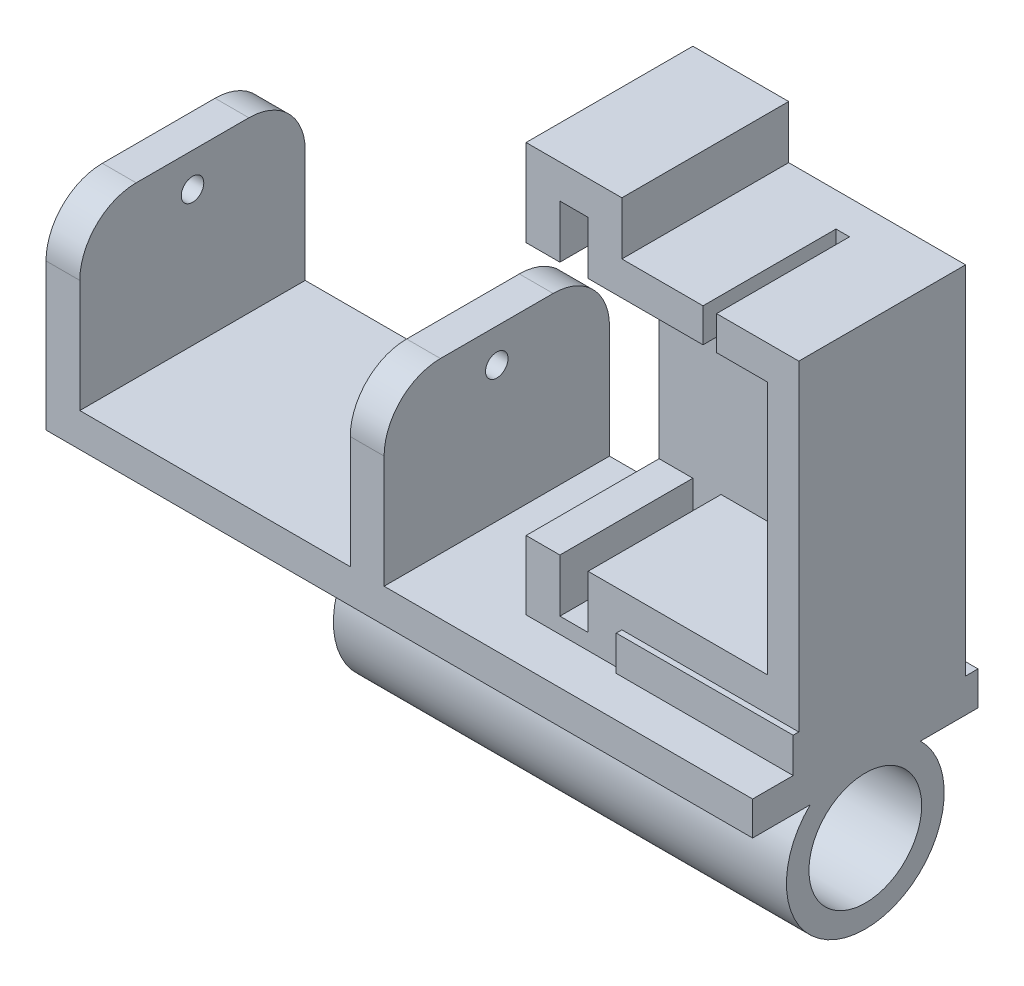
SolidWorks part; units mm, degrees
ref_plane "Front Plane" through (0, 0, 0) normal (0, 0, 1) x (1, 0, 0)
ref_plane "Top Plane" through (0, 0, 0) normal (0, 1, 0) x (1, 0, 0)
ref_plane "Right Plane" through (0, 0, 0) normal (1, 0, 0) x (0, 0, -1)
sketch "Sketch1" plane through (0, 0, 0) normal (0, 1, 0) x (1, 0, 0)
  line L1 (0, 0) -> (50, 0)
  line L2 (0, 0) -> (0, -20)
  line L3 (0, -20) -> (50, -20)
  line L4 (50, 0) -> (50, -20)
  dimension "D1" = 20
  dimension "D2" = 50
extrude "Boss-Extrude1" add sketch "Sketch1" along normal blind 3
sketch "Sketch2" plane through (0, 3, 0) normal (0, 1, 0) x (1, 0, 0)
  line L0 (0, -20) -> (50, -20) construction
  line L1 (0, 0) -> (3, 0)
  line L2 (0, 0) -> (0, -20)
  line L3 (0, -20) -> (3, -20)
  line L4 (3, 0) -> (3, -20)
  dimension "D1" = 3
extrude "Boss-Extrude2" add sketch "Sketch2" along normal blind 15
sketch "Sketch3" plane through (3, 0, 0) normal (1, 0, 0) x (0, 0, -1)
  circle A0 centre (-10, 15) radius 1
  dimension "D1" = 2
  dimension "D2" = 12
  dimension "D3" = 10
extrude "Cut-Extrude1" cut sketch "Sketch3" against normal blind 15
fillet "Fillet1" radius 5 2 edges at (1.5, 18, 0) (1.5, 18, 20)
sketch "Sketch4" plane through (0, 3, 0) normal (0, 1, 0) x (1, 0, 0)
  line L0 (3, -20) -> (50, -20) construction
  line L1 (27, -20) -> (30, -20)
  line L2 (27, -20) -> (27, 0)
  line L3 (27, 0) -> (30, 0)
  line L4 (30, -20) -> (30, 0)
  line L5 (50, 0) -> (3, 0) construction
  dimension "D1" = 3
  dimension "D2" = 30
extrude "Boss-Extrude3" add sketch "Sketch4" along normal blind 15
sketch "Sketch5" plane through (27, 0, 0) normal (-1, 0, 0) x (0, 0, 1)
  circle A0 centre (10, 15) radius 1
extrude "Cut-Extrude2" cut sketch "Sketch5" against normal blind 15
fillet "Fillet2" radius 5 2 edges at (28.5, 18, 20) (28.5, 18, 0)
ref_plane "Plane1" through (0, 0, 10) normal (0, 0, -1) x (-1, 0, 0)
sketch "Sketch6" plane through (0, 0, 10) normal (0, 0, -1) x (-1, 0, 0)
  line L0 (-3, 15) -> (-37.0484, 15)
  line L1 (-3, 16) -> (-3, 14) construction
  line L2 (-30, 12.7) -> (-30, 17.3)
  line L3 (-62.9, 34.6) -> (-47, 34.6)
  line L4 (-30, 17.3) -> (-33.2, 17.3)
  line L5 (-33.2, 17.3) -> (-33.2, 23.8)
  line L6 (-33.2, 23.8) -> (-37.2, 23.8)
  line L7 (-30, 12.7) -> (-33.2, 12.7)
  line L8 (-33.2, 12.7) -> (-33.2, 9.1)
  line L9 (-33.2, 9.1) -> (-41.5, 9.1)
  line L10 (-41.5, 9.1) -> (-41.5, 4.4)
  line L11 (-41.5, 4.4) -> (-44, 4.4)
  line L12 (-44, 4.4) -> (-44, 9.1)
  line L13 (-44, 9.1) -> (-59.9, 9.1)
  line L14 (-59.9, 9.1) -> (-59.9, 31.6)
  line L15 (-59.9, 31.6) -> (-44, 31.6)
  line L16 (-44, 31.6) -> (-44, 36.3)
  line L17 (-44, 36.3) -> (-41.5, 36.3)
  line L18 (-41.5, 36.3) -> (-41.5, 31.6)
  line L19 (-41.5, 31.6) -> (-37.2, 31.6)
  line L20 (-37.2, 31.6) -> (-37.2, 23.8)
  line L21 (-47, 34.6) -> (-47, 39.3)
  line L22 (-47, 39.3) -> (-38.5, 39.3)
  line L23 (-38.5, 39.3) -> (-38.5, 34.6)
  line L24 (-38.5, 34.6) -> (-34.2, 34.6)
  line L25 (-34.2, 34.6) -> (-34.2, 26.8)
  line L26 (-30.2, 26.8) -> (-34.2, 26.8)
  line L27 (-30.2, 20.3) -> (-30.2, 26.8)
  line L28 (-27, 20.3) -> (-30.2, 20.3)
  line L29 (-27, 9.7) -> (-27, 20.3)
  line L30 (-27, 9.7) -> (-30.2, 9.7)
  line L31 (-30.2, 9.7) -> (-30.2, 6.1)
  line L32 (-30.2, 6.1) -> (-38.5, 6.1)
  line L33 (-38.5, 6.1) -> (-38.5, 1.4)
  line L34 (-38.5, 1.4) -> (-47, 1.4)
  line L35 (-47, 1.4) -> (-47, 6.1)
  line L36 (-47, 6.1) -> (-62.9, 6.1)
  line L37 (-62.9, 6.1) -> (-62.9, 34.6)
  line L38 (-54.2, 31.6) -> (-54.2, 34.6)
  line L39 (-54.2, 34.6) -> (-55.4, 34.6)
  line L40 (-55.4, 34.6) -> (-55.4, 31.6)
  line L41 (-38.5, 6.1) -> (-38.5, 9.1)
  line L42 (-38.5, 34.6) -> (-38.5, 31.6)
  point P9 (-30, 15)
  point P41 (-55.4, 31.6)
  point P42 (-54.2, 31.6)
  dimension "D1" = 5.9
  dimension "D2" = 3.2
  dimension "D3" = 4.6
  dimension "D4" = 26.7
  dimension "D5" = 22.5
  dimension "D6" = 15.9
  dimension "D7" = 4.7
  dimension "D8" = 4.7
  dimension "D9" = 2.5
  dimension "D10" = 2.5
  dimension "D11" = 4.7
  dimension "D12" = 22.7
  dimension "D13" = 7.8
  dimension "D14" = 15.9
  dimension "D15" = 4
  dimension "D17" = 4.5
  dimension "D18" = 1.2
  dimension "D16" = 3
extrude "Boss-Extrude4" add sketch "Sketch6" along normal mid plane 11.8 contours L42 L23 L22 L21 L3 L38 L15 L16 L17 L18 L19 | L33 L41 L9 L10 L11 L12 L13 L14 L15 L40 L3 L37 L36 L35 L34
sketch "Sketch7" plane through (50, 0, 0) normal (1, 0, 0) x (0, 0, -1)
  line L1 (0, 3) -> (-20, 3)
  line L2 (0, 3) -> (0, 0)
  line L3 (0, 0) -> (-20, 0)
  line L4 (-20, 3) -> (-20, 0)
extrude "Boss-Extrude5" add sketch "Sketch7" along normal blind 12.8
sketch "Sketch8" plane through (0, 0, 10) normal (0, 0, -1) x (-1, 0, 0)
  line L1 (-47, 6.1) -> (-62.8, 6.1)
  line L2 (-47, 6.1) -> (-47, 3)
  line L3 (-47, 3) -> (-62.8, 3)
  line L4 (-62.8, 6.1) -> (-62.8, 3)
extrude "Boss-Extrude6" add sketch "Sketch8" along normal mid plane 12.8
sketch "Sketch9" plane through (0, 0, 4.1) normal (0, 0, -1) x (-1, 0, 0)
  line L0 (-38.5, 3) -> (-38.5, 39.3)
  line L1 (-38.5, 39.3) -> (-47, 39.3)
  line L2 (-47, 39.3) -> (-47, 34.6)
  line L3 (-47, 34.6) -> (-62.9, 34.6)
  line L4 (-62.9, 34.6) -> (-62.8, 3)
  line L5 (-62.8, 3) -> (-38.5, 3)
extrude "Boss-Extrude7" add sketch "Sketch9" along normal blind 3
sketch "Sketch10" plane through (62.9, 0, 0) normal (1, 0, 0) x (0, 0, -1)
  line L1 (-31.2329, 48.6115) -> (12.4563, 48.6115)
  line L2 (-31.2329, 48.6115) -> (-31.2329, -11.0665)
  line L3 (-31.2329, -11.0665) -> (12.4563, -11.0665)
  line L4 (12.4563, 48.6115) -> (12.4563, -11.0665)
  line L5 (-31.2329, 48.6115) -> (12.4563, -11.0665) construction
  line L6 (-31.2329, -11.0665) -> (12.4563, 48.6115) construction
  point P0 (-9.3883, 18.7725)
extrude "Cut-Extrude4" cut sketch "Sketch10" against normal blind 0.2
sketch "Sketch11" plane through (62.7, 0, 0) normal (1, 0, 0) x (0, 0, -1)
  line L0 (-10, -12.0671) -> (-10, 12.0671) construction
  line L1 (-20, 0) -> (0, 0) construction
  circle A0 centre (-10, -5) radius 5
  circle A1 centre (-10, -5) radius 7
  dimension "D1" = 10
  dimension "D2" = 2
extrude "Boss-Extrude8" add sketch "Sketch11" against normal blind 40.2
